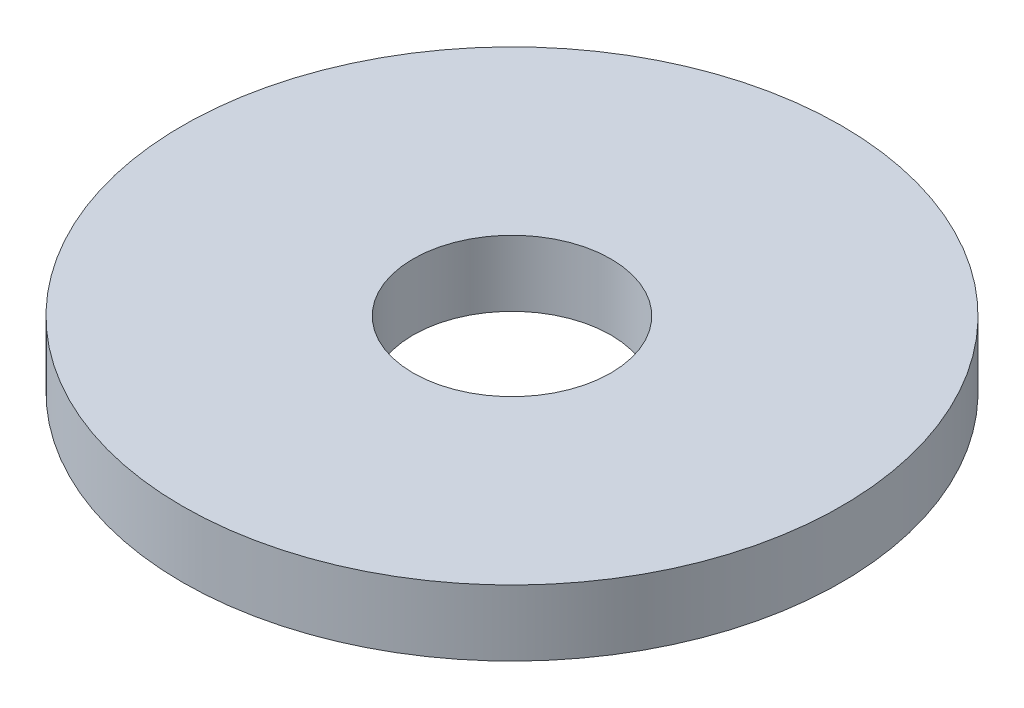
SolidWorks part; units mm, degrees
ref_plane "前视基准面" through (0, 0, 0) normal (0, 0, 1) x (1, 0, 0)
ref_plane "上视基准面" through (0, 0, 0) normal (0, 1, 0) x (1, 0, 0)
ref_plane "右视基准面" through (0, 0, 0) normal (1, 0, 0) x (0, 0, -1)
sketch "草图1" plane through (0, 0, 0) normal (0, 1, 0) x (1, 0, 0)
  circle A0 centre (0, 0) radius 1.5
  circle A1 centre (0, 0) radius 5
  dimension "D1" = 3
  dimension "D2" = 10
extrude "凸台-拉伸3" add sketch "草图1" along normal blind 1
